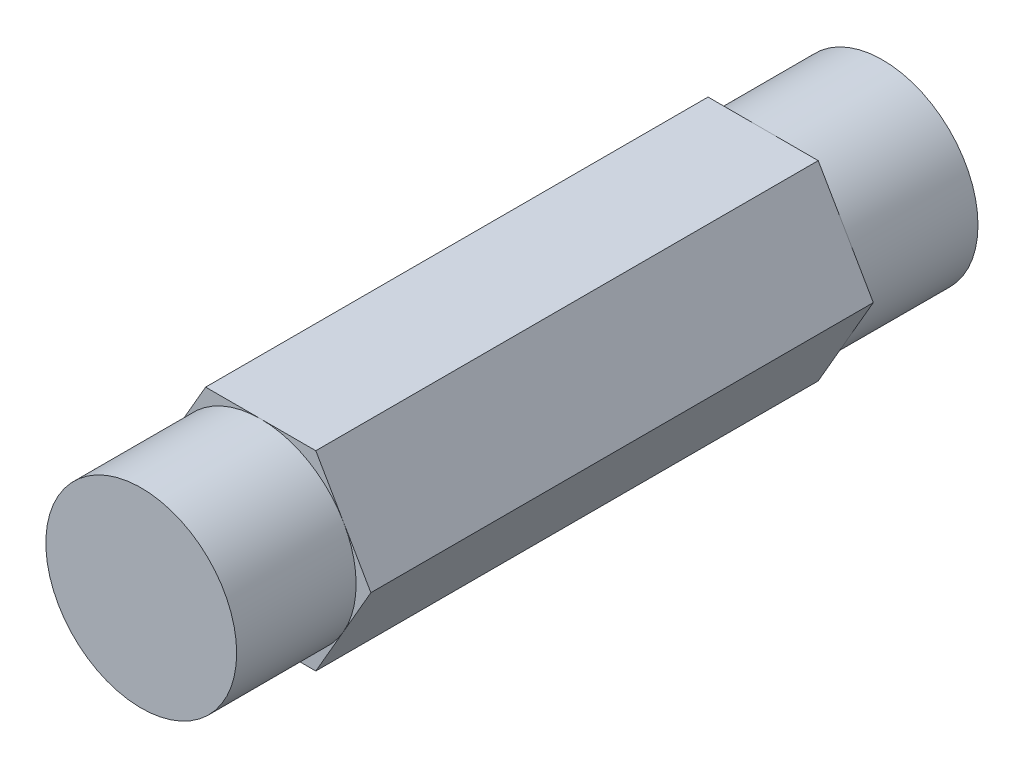
SolidWorks part; units mm, degrees
ref_plane "Front Plane" through (0, 0, 0) normal (0, 0, 1) x (1, 0, 0)
ref_plane "Top Plane" through (0, 0, 0) normal (0, 1, 0) x (1, 0, 0)
ref_plane "Right Plane" through (0, 0, 0) normal (1, 0, 0) x (0, 0, -1)
sketch "Sketch1" plane through (0, 0, 0) normal (0, 0, 1) x (1, 0, 0)
  line L1 (7.3323, 0) -> (3.6662, 6.35)
  line L2 (3.6662, 6.35) -> (-3.6662, 6.35)
  line L3 (-3.6662, 6.35) -> (-7.3323, 0)
  line L4 (-7.3323, 0) -> (-3.6662, -6.35)
  line L5 (-3.6662, -6.35) -> (3.6662, -6.35)
  line L6 (3.6662, -6.35) -> (7.3323, 0)
  circle A0 centre (0, 0) radius 6.35 construction
  dimension "D1" = 12.7
extrude "Boss-Extrude1" add sketch "Sketch1" along normal mid plane 49.3395
sketch "Sketch4" plane through (0, 0, 24.6697) normal (0, 0, 1) x (1, 0, 0)
  circle A0 centre (0, 0) radius 6.35
extrude "Cut-Extrude2" cut sketch "Sketch4" against normal blind 7.9502 flip side to cut
mirror "Mirror1" about plane through (0, 0, 0) normal (0, 0, 1) of "Cut-Extrude2"
equation "\"D1@Boss-Extrude1\"=1.9375in+0.005"
